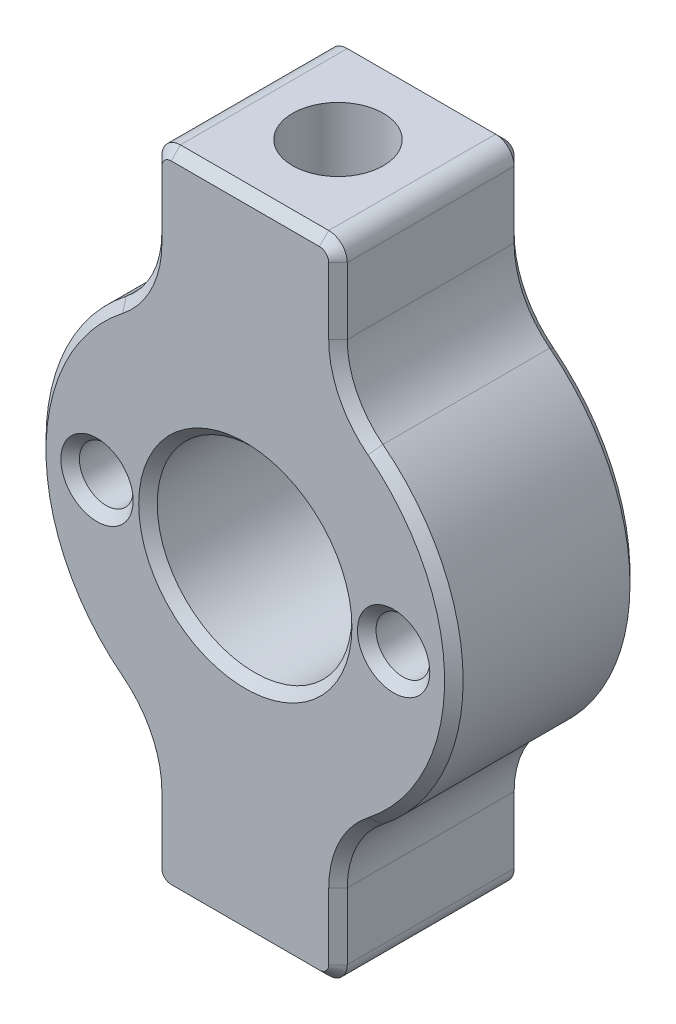
SolidWorks part; units mm, degrees
ref_plane "Front" through (0, 0, 0) normal (0, 0, 1) x (1, 0, 0)
ref_plane "Top" through (0, 0, 0) normal (0, 1, 0) x (1, 0, 0)
ref_plane "Right" through (0, 0, 0) normal (1, 0, 0) x (0, 0, -1)
sketch "Skizze1" plane through (0, 0, 0) normal (0, 0, 1) x (1, 0, 0)
  circle A0 centre (0, 0) radius 5.25
  circle A1 centre (0, 0) radius 11.25
  dimension "D1" = 10.5
  dimension "D2" = 6
extrude "Aufsatz-Linear austragen1" add sketch "Skizze1" along normal blind 10
sketch "Skizze2" plane through (0, 0, 0) normal (0, 1, 0) x (1, 0, 0)
  line L0 (0, 0) -> (0, -10) construction
  line L3 (-11.25, -10) -> (11.25, -10) construction
  line L4 (5.25, 0) -> (-5.25, 0) construction
  line L5 (-5, -10) -> (5, -10)
  line L6 (-5, -10) -> (-5, 0)
  line L7 (-5, 0) -> (5, 0)
  line L8 (5, -10) -> (5, 0)
  line L9 (-5, -10) -> (5, 0) construction
  line L10 (-5, 0) -> (5, -10) construction
  point P4 (0, -5)
extrude "Aufsatz-Linear austragen2" add sketch "Skizze2" along normal blind 11.4 from offset 6
sketch "Skizze3" plane through (0, 17.4, 0) normal (0, 1, 0) x (1, 0, 0)
  line L0 (0, 0) -> (0, -10) construction
  line L1 (-5, -10) -> (5, -10) construction
  circle A0 centre (0, -5) radius 2.45
  dimension "D1" = 4.9
extrude "Schnitt-Linear austragen1" cut sketch "Skizze3" against normal blind 10
mirror "Spiegeln1" about plane through (0, 0, 0) normal (0, 1, 0) of "Schnitt-Linear austragen1", "Aufsatz-Linear austragen2"
sketch "Skizze4" plane through (0, 0, 10) normal (0, 0, 1) x (1, 0, 0)
  line L0 (0, 0) -> (0, 11.1324) construction
  line L1 (0, 0) -> (13.0739, 0) construction
  circle A2 centre (8, 0) radius 1.45
  circle A3 centre (-8, 0) radius 1.45
  dimension "D1" = 16
  dimension "D2" = 2.9
extrude "Schnitt-Linear austragen2" cut sketch "Skizze4" against normal blind 8
fillet "Verrundung2" radius 5 4 edges at (-5, -10.0778, 5) (-5, 10.0778, 5) (5, 10.0778, 5) (5, -10.0778, 5)
fillet "Verrundung1" radius 1 4 edges at (-5, 17.4, 5) (5, 17.4, 5) (5, -17.4, 5) (-5, -17.4, 5)
chamfer "Fase1" distance 0.5 angle 45 36 edges at (-5, 14.6043, 10) (-5, -14.6043, 10) (0, -17.4, 10) (5, -14.6043, 10) (5, 14.6043, 10) (-4.7071, -17.1071, 10) (4.7071, -17.1071, 10) (4.7071, 17.1071, 10) (-4.7071, 17.1071, 10) (-5, 14.6043, 0) (5, -14.6043, 0) (0, -17.4, 0) (-5, -14.6043, 0) (5, 14.6043, 0) (-4.7071, -17.1071, 0) (4.7071, -17.1071, 0) (4.7071, 17.1071, 0) (-4.7071, 17.1071, 0) (5.25, 0, 0) (5.25, 0, 10) (9.45, 0, 10) (-9.45, 0, 10) (-11.25, 0, 0) (-11.25, 0, 10) (11.25, 0, 10) (11.25, 0, 0) (-5.5064, -10.616, 10) (-5.5064, -10.616, 0) (-5.5064, 10.616, 10) (-5.5064, 10.616, 0) (5.5064, 10.616, 0) (5.5064, 10.616, 10) (5.5064, -10.616, 0) (5.5064, -10.616, 10) (0, 17.4, 0) (0, 17.4, 10)
